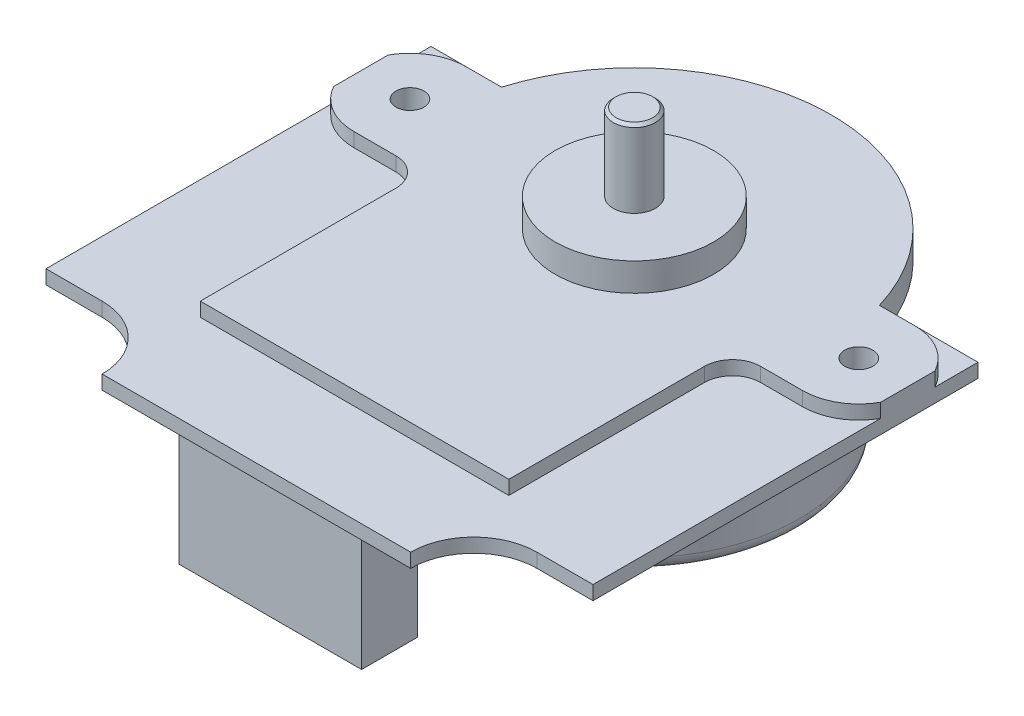
SolidWorks part; units mm, degrees
ref_plane "前视基准面" through (0, 0, 0) normal (0, 0, 1) x (1, 0, 0)
ref_plane "上视基准面" through (0, 0, 0) normal (0, 1, 0) x (1, 0, 0)
ref_plane "右视基准面" through (0, 0, 0) normal (1, 0, 0) x (0, 0, -1)
sketch "草图1" plane through (0, 0, 0) normal (0, 1, 0) x (1, 0, 0)
  line L0 (0, 31.7037) -> (0, 0) construction
  line L1 (-19.5, 15.975) -> (-13.1302, 15.975)
  line L2 (-19.5, 15.975) -> (-19.5, -11.475)
  line L3 (-11, -15.975) -> (11, -15.975)
  line L4 (19.5, 15.975) -> (19.5, -11.475)
  line L5 (-19.5, 15.975) -> (19.5, -15.975) construction
  line L6 (-19.5, -15.975) -> (0.6494, 0.532) construction
  line L7 (0, 10.975) -> (16.8947, 10.975) construction
  line L8 (0.5012, 0.4106) -> (19.5, 15.975) construction
  line L9 (13.1302, 15.975) -> (19.5, 15.975)
  line L10 (15.5, -11.475) -> (19.5, -11.475)
  line L11 (-15.5, -11.475) -> (-19.5, -11.475)
  line L12 (-19.5, -11.475) -> (-19.5, -15.975) construction
  line L13 (-19.5, -15.975) -> (-11, -15.975) construction
  line L14 (19.5, -15.975) -> (19.5, -11.475) construction
  line L15 (11, -15.975) -> (19.5, -15.975) construction
  arc A0 (13.1302, 15.975) -> (-13.1302, 15.975) centre (0, 10.975) ccw
  circle A1 centre (16, 10.975) radius 1
  circle A2 centre (0, 10.975) radius 11.8 construction
  circle A3 centre (-16, 10.975) radius 1
  arc A4 (15.5, -11.475) -> (11, -15.975) centre (15.5, -15.975) ccw
  arc A5 (-15.5, -11.475) -> (-11, -15.975) centre (-15.5, -15.975) cw
  circle A6 centre (0, 10.975) radius 5.65 construction
  point P0 (0, 0)
  point P10 (0, 25.025)
  dimension "D3" = 32
  dimension "D4" = 2
  dimension "D6" = 23.6
  dimension "D7" = 19.7
  dimension "D9" = 4
  dimension "D10" = 11.3
  dimension "D1" = 41
  dimension "D2" = 39
  dimension "D5" = 5
  dimension "D8" = 4.5
extrude "凸台-拉伸1" add sketch "草图1" along normal blind 2
sketch "草图2" plane through (0, 2, 0) normal (0, 1, 0) x (1, 0, 0)
  circle A0 centre (0, 10.975) radius 5.65
  dimension "D1" = 11.3
extrude "凸台-拉伸2" add sketch "草图2" along normal blind 2
sketch "草图3" plane through (0, 4, 0) normal (0, 1, 0) x (1, 0, 0)
  circle A0 centre (0, 10.975) radius 1.5
  dimension "D1" = 3
extrude "凸台-拉伸3" add sketch "草图3" along normal blind 5.5 and the other way blind 15
sketch "草图4" plane through (0, 0, 0) normal (1, 0, 0) x (0, 0, -1)
  line L0 (9.475, -11) -> (12.475, -11) construction
  line L1 (10.975, -11) -> (-0.825, -11)
  line L2 (10.975, -11) -> (10.975, -3)
  line L3 (10.975, -3) -> (-0.825, -3)
  line L4 (-0.825, -11) -> (-0.825, -3)
  line L5 (10.975, 9.5) -> (10.975, -11) construction
  line L6 (12.475, 9.5) -> (9.475, 9.5) construction
  line L7 (-11.475, 0) -> (15.975, 0) construction
  dimension "D1" = 23.6
  dimension "D2" = 3
revolve "旋转1" add sketch "草图4" angle 360 about L5
fillet "圆角1" radius 1 1 edges at (0, -11, 0.825)
sketch "草图5" plane through (0, 2, 0) normal (0, 1, 0) x (1, 0, 0)
  line L0 (0, 30.4665) -> (0, 0) construction
  line L1 (0, 0) -> (0, -20.3242) construction
  line L2 (-11, -8.975) -> (11, -8.975)
  line L3 (11, -8.975) -> (11, 6.975)
  line L6 (-11, -15.975) -> (11, -15.975) construction
  line L16 (-11, -8.975) -> (-11, 6.975)
  line L18 (0, 10.975) -> (-23.1924, 10.975) construction
  line L19 (0, 32.8516) -> (0, 10.975) construction
  line L20 (0, 31.7037) -> (0, 0) construction
  line L21 (-16, 6.975) -> (-11, 6.975)
  line L22 (13.4686, 14.975) -> (16, 14.975)
  line L23 (-16, 14.975) -> (-13.4686, 14.975)
  line L24 (11, 6.975) -> (16, 6.975)
  arc A4 (-16, 14.975) -> (-16, 6.975) centre (-16, 10.975) ccw
  arc A5 (16, 14.975) -> (16, 6.975) centre (16, 10.975) cw
  arc A7 (13.4686, 14.975) -> (-13.4686, 14.975) centre (0, 10.975) ccw
  point P34 (0, 6.975)
  point P36 (0, 14.975)
  dimension "D4" = 8
  dimension "D5" = 40
  dimension "D1" = 7
  dimension "D2" = 11
extrude "切除-拉伸4" cut sketch "草图5" against normal blind 1 flip side to cut
fillet "圆角2" radius 2 2 edges at (11, 1.5, -6.975) (-11, 1.5, -6.975)
chamfer "倒角1" distance 0.2 angle 45 2 edges at (0, -3, 0.825) (0, 9.5, -9.475)
sketch "草图6" plane through (0, 0, 0) normal (0, -1, 0) x (1, 0, 0)
  line L0 (0, 0) -> (0, 18.6407) construction
  line L1 (-11, 15.975) -> (11, 15.975) construction
  line L2 (-6.5, 14.975) -> (6.5, 14.975)
  line L3 (-6.5, 14.975) -> (-6.5, 10.975)
  line L4 (-6.5, 10.975) -> (6.5, 10.975)
  line L5 (6.5, 14.975) -> (6.5, 10.975)
  line L6 (-6.5, 14.975) -> (6.5, 10.975) construction
  line L7 (-6.5, 10.975) -> (6.5, 14.975) construction
  point P4 (0, 12.975)
  dimension "D1" = 13
  dimension "D2" = 1
  dimension "D3" = 4
extrude "凸台-拉伸4" add sketch "草图6" along normal blind 9
